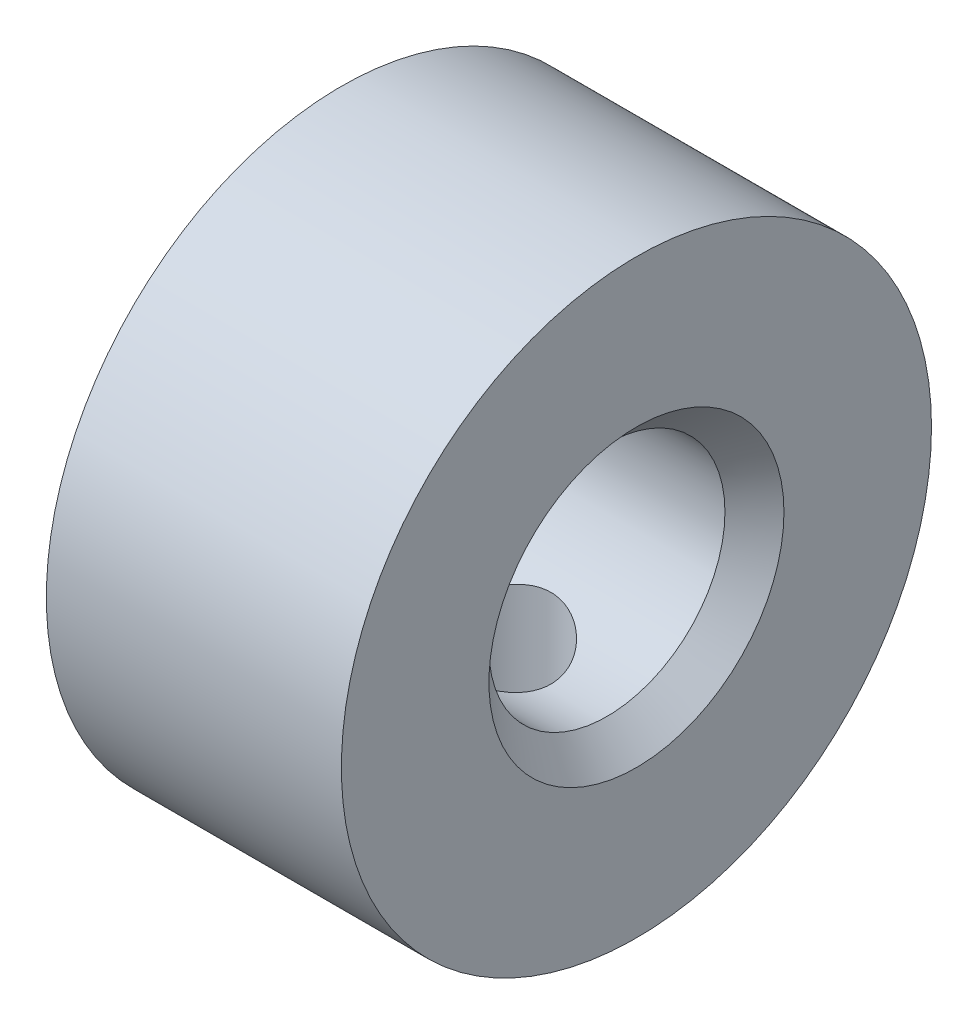
SolidWorks part; units mm, degrees
material "5052-H32"
ref_plane "Front Plane" through (0, 0, 0) normal (0, 0, 1) x (1, 0, 0)
ref_plane "Top Plane" through (0, 0, 0) normal (0, 1, 0) x (1, 0, 0)
ref_plane "Right Plane" through (0, 0, 0) normal (1, 0, 0) x (0, 0, -1)
sketch "Sketch1" plane through (0, 0, 0) normal (0, 0, 1) x (1, 0, 0)
  line L0 (0, 10) -> (0, 0)
  line L1 (0, 0) -> (10, 0)
  line L2 (10, 0) -> (10, 10)
  line L3 (10, 10) -> (0, 10)
  line L4 (0, 0) -> (10, 0) construction
revolve "Revolve1" add sketch "Sketch1" angle 360 about L4
hole_wizard "Ø8.0 (8) Diameter Hole1" positions "Sketch3" profile "Sketch2" hole size "Ø8.0" standard "ANSI Metric"
sketch "Sketch3" plane through (0, 0, 0) normal (-1, 0, 0) x (0, 0, 1)
  point P0 (0, 0)
sketch "Sketch2" plane through (0, 0, 0) normal (0, 1, 0) x (0, 0, 1)
  line L0 (0, 0) -> (0, 10)
  line L1 (0, 10) -> (4, 10)
  line L2 (4, 10) -> (4, 0)
  line L5 (4, 0) -> (0, 0)
  line L11 (0, -6.35) -> (0, 107.95) construction
  dimension "Thru Hole Dia." = 8
  dimension "Thru Hole Depth" = 10
ref_plane "Plane1" through (0, -3.4038, 0) normal (0, 1, 0) x (1, 0, 0)
hole_wizard "M5x0.8 Tapped Hole1" positions "Sketch5" profile "Sketch4" tap size "M5x0.8" standard "ANSI Metric"
sketch "Sketch5" plane through (0, -3.4038, 0) normal (0, 1, 0) x (1, 0, 0)
  point P0 (5, 0.0009)
sketch "Sketch4" plane through (5, -3.4038, -0.0009) normal (1, 0, 0) x (0, 0, 1)
  line L0 (0, 0) -> (0, 6.5962)
  line L1 (0, 6.5962) -> (2.1, 6.5962)
  line L2 (2.1, 6.5962) -> (2.1, 0)
  line L5 (2.1, 0) -> (0, 0)
  line L11 (0, -6.35) -> (0, 107.95) construction
  dimension "Thread Major Dia." = 4.2
  dimension "Thru Tap Drill Depth" = 6.5962
chamfer "Chamfer1" distance 1 angle 45 2 edges at (10, 0, 4) (0, 0, 4)
